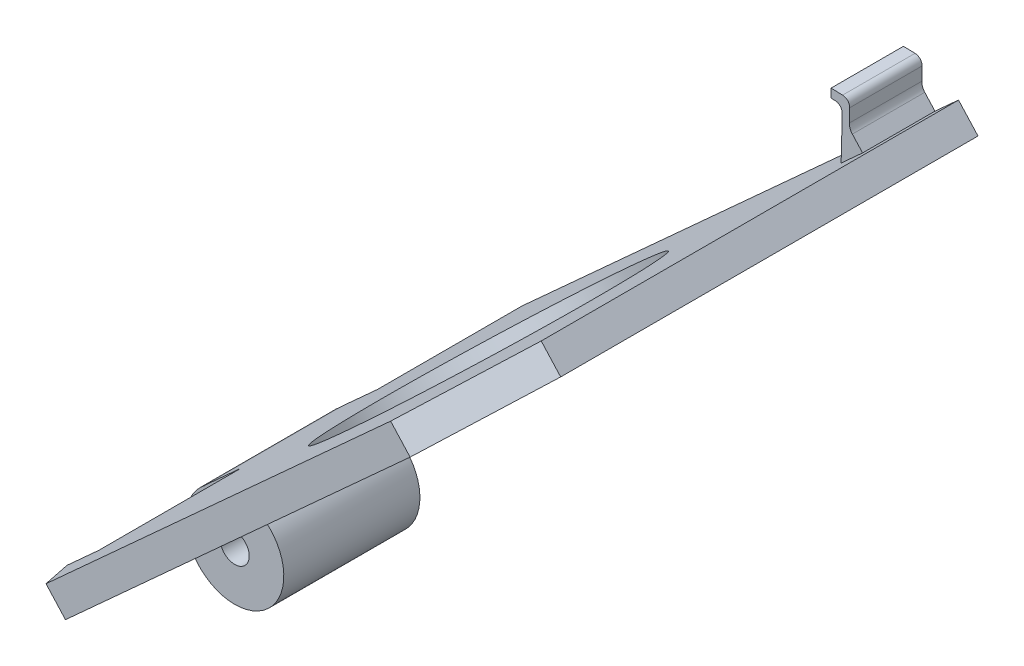
SolidWorks part; units mm, degrees
ref_plane "Plan de face" through (0, 0, 0) normal (0, 0, 1) x (1, 0, 0)
ref_plane "Plan de dessus" through (0, 0, 0) normal (0, 1, 0) x (1, 0, 0)
ref_plane "Plan de droite" through (0, 0, 0) normal (1, 0, 0) x (0, 0, -1)
sketch "Esquisse1" plane through (-56.0953, 61.7411, 0) normal (0.6725, -0.7401, 0) x (0, 0, 1)
  line L0 (-48.271, 18.5492) -> (-19.0228, 18.5492) construction
  line L1 (-19.0228, 18.5492) -> (-12.871, 24.701) construction
  line L2 (-12.871, 24.701) -> (-12.871, 57.111) construction
  line L3 (-12.871, 57.111) -> (-19.0228, 63.2628) construction
  line L5 (-48.271, 59.8728) -> (-48.271, 18.5492) construction
  line L6 (-19.0228, 63.2628) -> (-19.0228, 59.8728) construction
  line L7 (-19.0228, 59.8728) -> (-28.271, 59.8728) construction
  line L8 (-28.271, 59.8728) -> (-19.0228, 59.8728) construction
  line L9 (-28.271, 59.8728) -> (-28.271, 63.2628) construction
  line L10 (-28.271, 63.2628) -> (-38.271, 63.2628) construction
  line L12 (-38.271, 63.2628) -> (-38.271, 59.8728) construction
  line L13 (-38.271, 59.8728) -> (-48.271, 59.8728) construction
  line L14 (-48.271, 59.8728) -> (-38.271, 59.8728) construction
  line L15 (-13.171, 24.8253) -> (-13.171, 56.9867)
  line L16 (-13.171, 56.9867) -> (-18.7228, 62.5386)
  line L17 (-18.7228, 62.5386) -> (-18.7228, 59.5728)
  line L18 (-18.7228, 59.5728) -> (-28.571, 59.5728)
  line L19 (-28.571, 59.5728) -> (-28.571, 62.9628)
  line L20 (-28.571, 62.9628) -> (-37.971, 62.9628)
  line L21 (-37.971, 62.9628) -> (-37.971, 59.5728)
  line L22 (-37.971, 59.5728) -> (-47.971, 59.5728)
  line L23 (-47.971, 59.5728) -> (-47.971, 18.8492)
  line L24 (-47.971, 18.8492) -> (-19.1471, 18.8492)
  line L25 (-19.1471, 18.8492) -> (-13.171, 24.8253)
  dimension "D1" = 0.3
extrude "Boss.-Extru.1" add sketch "Esquisse1" against normal blind 2
sketch "Esquisse2" plane through (0, 0, -37.971) normal (0, 0, -1) x (-1, 0, 0)
  circle A0 centre (101.9837, 18.1708) radius 1
  circle A1 centre (101.9837, 18.1708) radius 3.3906
extrude "Boss.-Extru.2" add sketch "Esquisse2" against normal up to surface (9.4 mm away) up to face at (-102.1143, 21.2813, -28.571)
sketch "Esquisse3" plane through (-56.0953, 61.7411, 0) normal (0.6725, -0.7401, 0) x (0, 0, -1)
  line L0 (47.971, -39.211) -> (13.171, -39.211) construction
  line L1 (47.971, -59.5728) -> (47.971, -18.8492) construction
  line L2 (13.171, -24.8253) -> (13.171, -56.9867) construction
  circle A0 centre (30.571, -39.211) radius 10
  dimension "D1" = 20
extrude "Enlèv. mat.-Extru.1" cut sketch "Esquisse3" against normal blind 2
sketch "Esquisse4" plane through (0, 0, -47.971) normal (0, 0, -1) x (-1, 0, 0)
  line L0 (73.9312, 50.4001) -> (73.9076, 51.3252)
  line L1 (73.0194, 49.0668) -> (74.4997, 47.7219)
  line L2 (101.5322, 23.1613) -> (71.3911, 50.5462) construction
  line L5 (75.1947, 51.8582) -> (75.21, 51.2582)
  line L7 (74.4227, 50.738) -> (74.4997, 47.7219)
  line L8 (73.7236, 49.8418) -> (73.0194, 49.0668)
  line L10 (78.3536, 46.8848) -> (78.1091, 47.1179) construction
  line L11 (71.3911, 50.5462) -> (70.0462, 49.0659) construction
  line L12 (74.3947, 51.8378) -> (75.1947, 51.8582)
  line L13 (74.4074, 51.338) -> (73.9076, 51.3252) construction
  line L14 (74.4074, 51.338) -> (74.3947, 51.8378) construction
  line L15 (75.21, 51.2582) -> (74.9098, 51.2506)
  arc A0 (73.9076, 51.3252) -> (74.3947, 51.8378) centre (74.4074, 51.338) cw
  arc A2 (73.7236, 49.8418) -> (73.9312, 50.4001) centre (73.1315, 50.3797) ccw
  arc A3 (74.9098, 51.2506) -> (74.4227, 50.738) centre (74.9226, 50.7508) ccw
  point P17 (79.8388, 47.4228)
  dimension "D3" = 0.5
  dimension "D4" = 0.5
  dimension "D6" = 0.8
  dimension "D11" = 0.9251
  dimension "D2" = 0.6
  dimension "D5" = 1.0471
  dimension "D7" = 0.5
  dimension "D8" = 2
  dimension "D9" = 1.6
  dimension "D10" = 0.8
  dimension "D12" = 2.2
extrude "Boss.-Extru.4" add sketch "Esquisse4" against normal blind 5
